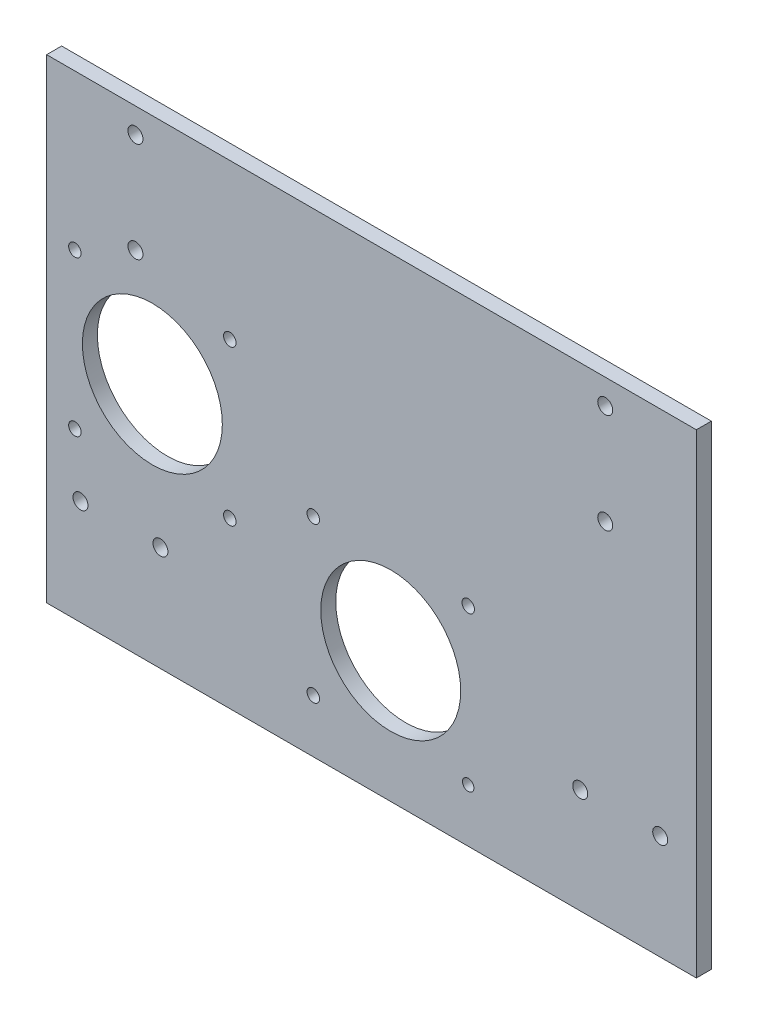
SolidWorks part; units mm, degrees
ref_plane "前视基准面" through (0, 0, 0) normal (0, 0, 1) x (1, 0, 0)
ref_plane "上视基准面" through (0, 0, 0) normal (0, 1, 0) x (1, 0, 0)
ref_plane "右视基准面" through (0, 0, 0) normal (1, 0, 0) x (0, 0, -1)
sketch "草图1" plane through (0, 0, 0) normal (0, 0, 1) x (1, 0, 0)
  line L1 (65, -47.5) -> (-65, -47.5)
  line L2 (65, -47.5) -> (65, 47.5)
  line L3 (65, 47.5) -> (-65, 47.5)
  line L4 (-65, -47.5) -> (-65, 47.5)
  line L5 (65, -47.5) -> (-65, 47.5) construction
  line L6 (65, 47.5) -> (-65, -47.5) construction
  point P0 (0, 0)
  dimension "D1" = 130
  dimension "D2" = 95
extrude "凸台-拉伸1" add sketch "草图1" along normal blind 3
sketch "草图2" plane through (0, 0, 3) normal (0, 0, 1) x (1, 0, 0)
  line L0 (0, -47.5) -> (0, -26.5) construction
  line L1 (-65, -47.5) -> (65, -47.5) construction
  line L2 (0, -26.5) -> (10, -26.5) construction
  circle A0 centre (10, -26.5) radius 1.5
  circle A1 centre (-10, -26.5) radius 1.5
  dimension "D3" = 3
  dimension "D1" = 21
  dimension "D2" = 10
sketch "草图3" plane through (0, 0, 0) normal (0, 0, -1) x (-1, 0, 0)
  circle A0 centre (-57.7671, -26.5) radius 1.5
  circle A1 centre (-41.7671, -26.5) radius 1.5
  circle A2 centre (42.2329, -26.5) radius 1.5
  circle A4 centre (58.2329, -26.5) radius 1.5
extrude "切除-拉伸2" cut sketch "草图3" against normal blind 10
sketch "草图4" plane through (0, 0, 0) normal (0, 0, -1) x (-1, 0, 0)
  circle A0 centre (-46.7671, 42.5) radius 1.5
  circle A1 centre (-46.7671, 22.5) radius 1.5
  circle A2 centre (47.2329, 42.5) radius 1.5
  circle A3 centre (47.2329, 22.5) radius 1.5
extrude "切除-拉伸3" cut sketch "草图4" against normal blind 10
sketch "草图5" plane through (0, 0, 0) normal (0, 0, -1) x (-1, 0, 0)
  circle A0 centre (-3.85, -21.35) radius 14
  circle A1 centre (43.85, 0.9967) radius 14
extrude "切除-拉伸4" cut sketch "草图5" against normal blind 10
sketch "草图6" plane through (0, 0, 3) normal (0, 0, 1) x (1, 0, 0)
  circle A0 centre (-59.35, 16.4967) radius 1.25
  circle A1 centre (-28.35, 16.4967) radius 1.25
  circle A2 centre (-59.35, -14.5033) radius 1.25
  circle A3 centre (-28.35, -14.5033) radius 1.25
  circle A4 centre (-11.65, -5.85) radius 1.25
  circle A5 centre (19.35, -5.85) radius 1.25
  circle A6 centre (19.35, -36.85) radius 1.1455
  circle A7 centre (-11.65, -36.85) radius 1.25
extrude "切除-拉伸5" cut sketch "草图6" against normal blind 10
